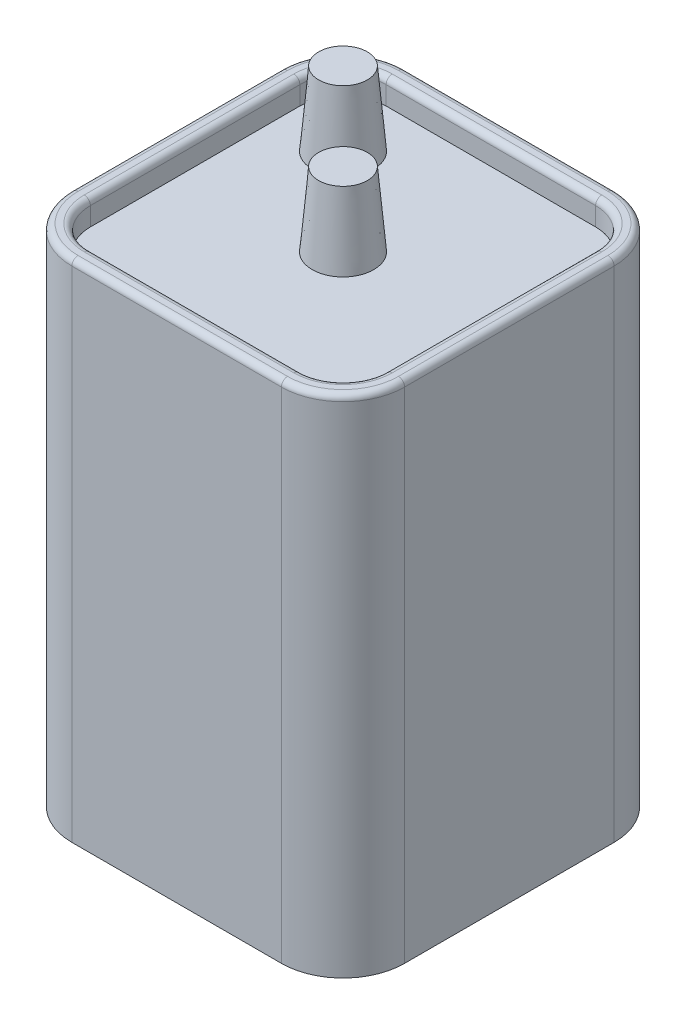
SolidWorks part; units mm, degrees
ref_plane "Front Plane" through (0, 0, 0) normal (0, 0, 1) x (1, 0, 0)
ref_plane "Top Plane" through (0, 0, 0) normal (0, 1, 0) x (1, 0, 0)
ref_plane "Right Plane" through (0, 0, 0) normal (1, 0, 0) x (0, 0, -1)
sketch "Sketch1" plane through (0, 0, 0) normal (0, 1, 0) x (1, 0, 0)
  line L1 (-34.29, 34.29) -> (34.29, 34.29)
  line L2 (-34.29, 34.29) -> (-34.29, -34.29)
  line L3 (-34.29, -34.29) -> (34.29, -34.29)
  line L4 (34.29, 34.29) -> (34.29, -34.29)
  line L5 (-34.29, 34.29) -> (34.29, -34.29) construction
  line L6 (-34.29, -34.29) -> (34.29, 34.29) construction
  point P0 (0, 0)
  dimension "D1" = 68.58
  dimension "D2" = 68.58
extrude "Boss-Extrude1" add sketch "Sketch1" along normal blind 104.14
fillet "Side Fillets" radius 12.7 4 edges at (-34.29, 52.07, -34.29) (34.29, 52.07, -34.29) (34.29, 52.07, 34.29) (-34.29, 52.07, 34.29)
sketch "Sketch2" plane through (0, 104.14, 0) normal (0, 1, 0) x (1, 0, 0)
  line L8 (21.59, 30.48) -> (-21.59, 30.48)
  line L9 (-30.48, 21.59) -> (-30.48, -21.59)
  line L10 (-21.59, -30.48) -> (21.59, -30.48)
  line L11 (30.48, -21.59) -> (30.48, 21.59)
  line L12 (21.59, 30.48) -> (-21.59, 30.48)
  line L13 (-30.48, 21.59) -> (-30.48, -21.59)
  line L14 (-21.59, -30.48) -> (21.59, -30.48)
  line L15 (30.48, -21.59) -> (30.48, 21.59)
  arc A8 (-21.59, 30.48) -> (-30.48, 21.59) centre (-21.59, 21.59) ccw
  arc A9 (-30.48, -21.59) -> (-21.59, -30.48) centre (-21.59, -21.59) ccw
  arc A10 (21.59, -30.48) -> (30.48, -21.59) centre (21.59, -21.59) ccw
  arc A11 (30.48, 21.59) -> (21.59, 30.48) centre (21.59, 21.59) ccw
  arc A12 (-21.59, 30.48) -> (-30.48, 21.59) centre (-21.59, 21.59) ccw
  arc A13 (-30.48, -21.59) -> (-21.59, -30.48) centre (-21.59, -21.59) ccw
  arc A14 (21.59, -30.48) -> (30.48, -21.59) centre (21.59, -21.59) ccw
  arc A15 (30.48, 21.59) -> (21.59, 30.48) centre (21.59, 21.59) ccw
  dimension "D1" = 3.81
extrude "Top Cut" cut sketch "Sketch2" against normal blind 5.08
fillet "Top Face Fillet" radius 1.27 16 edges at (30.5703, 104.14, -30.5703) (34.29, 104.14, 0) (30.5703, 104.14, 30.5703) (0, 104.14, 34.29) (-30.5703, 104.14, 30.5703) (-34.29, 104.14, 0) (-30.5703, 104.14, -30.5703) (0, 104.14, -34.29) (0, 104.14, -30.48) (-27.8762, 104.14, -27.8762) (-30.48, 104.14, 0) (-27.8762, 104.14, 27.8762) (0, 104.14, 30.48) (27.8762, 104.14, 27.8762) (30.48, 104.14, 0) (27.8762, 104.14, -27.8762)
sketch "Sketch-TERMINALS" plane through (0, 99.06, 0) normal (0, 1, 0) x (1, 0, 0)
  line L0 (-17.9605, 17.9605) -> (0, 0) construction
  line L1 (0, -37.719) -> (0, 37.719) construction
  circle A0 centre (0, 0) radius 6.35
  circle A1 centre (-17.9605, 17.9605) radius 6.35
  dimension "D1" = 12.7
  dimension "D2" = 25.4
  dimension "D3" = 45
extrude "Terminals" add sketch "Sketch-TERMINALS" along normal blind 15.24 draft 5
